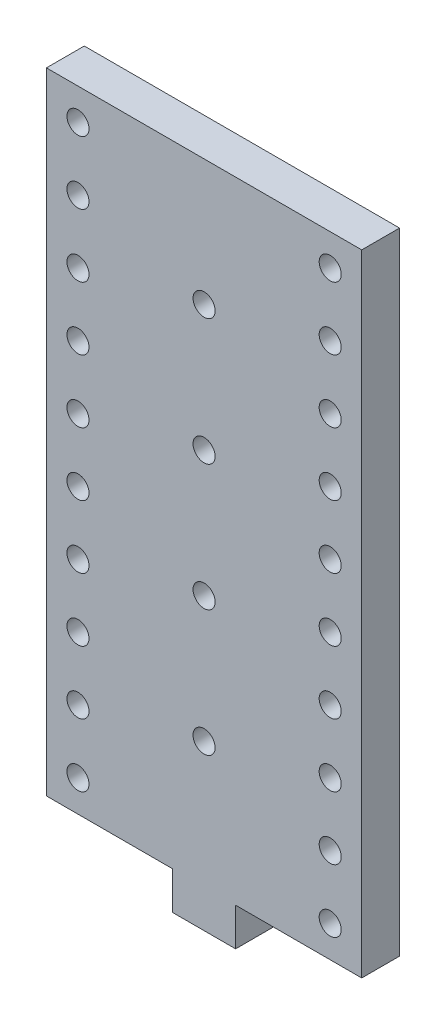
SolidWorks part; units mm, degrees
ref_plane "Plano frontal" through (0, 0, 0) normal (0, 0, 1) x (1, 0, 0)
ref_plane "Plano superior" through (0, 0, 0) normal (0, 1, 0) x (1, 0, 0)
ref_plane "Plano direito" through (0, 0, 0) normal (1, 0, 0) x (0, 0, -1)
sketch "Esboço1" plane through (0, 0, 0) normal (0, 0, 1) x (1, 0, 0)
  line L1 (20.6383, 0) -> (-29.3617, 0)
  line L2 (20.6383, 0) -> (20.6383, 100)
  line L3 (20.6383, 100) -> (-29.3617, 100)
  line L4 (-29.3617, 0) -> (-29.3617, 100)
  dimension "D1" = 100
  dimension "D2" = 50
extrude "Ressalto-extrusão1" add sketch "Esboço1" along normal blind 6
sketch "Esboço2" plane through (0, 0, 6) normal (0, 0, 1) x (1, 0, 0)
  line L0 (-24.3617, 100) -> (-24.3617, 0) construction
  line L1 (20.6383, 100) -> (-29.3617, 100) construction
  line L2 (-29.3617, 0) -> (20.6383, 0) construction
  line L3 (20.6383, 0) -> (20.6383, 100) construction
  line L4 (-29.3617, 100) -> (-29.3617, 0) construction
  line L6 (15.6383, 100.025) -> (15.6383, 0.025) construction
  circle A0 centre (-24.3617, 95) radius 1.75
  circle A1 centre (-24.3617, 85) radius 1.75
  circle A4 centre (-24.3617, 75) radius 1.75
  circle A5 centre (-24.3617, 65) radius 1.75
  circle A6 centre (-24.3617, 55) radius 1.75
  circle A7 centre (-24.3617, 45) radius 1.75
  circle A8 centre (-24.3617, 35) radius 1.75
  circle A9 centre (-24.3617, 25) radius 1.75
  circle A10 centre (-24.3617, 15) radius 1.75
  circle A11 centre (-24.3617, 5) radius 1.75
  circle A12 centre (15.6383, 95) radius 1.75
  circle A13 centre (15.6383, 85) radius 1.75
  circle A14 centre (15.6383, 75) radius 1.75
  circle A15 centre (15.6383, 65) radius 1.75
  circle A16 centre (15.6383, 55) radius 1.75
  circle A17 centre (15.6383, 45) radius 1.75
  circle A18 centre (15.6383, 35) radius 1.75
  circle A19 centre (15.6383, 25) radius 1.75
  circle A20 centre (15.6383, 15) radius 1.75
  circle A21 centre (15.6383, 5) radius 1.75
  dimension "D2" = 3.5
  dimension "D5" = 3.5
  dimension "D6" = 3.5
  dimension "D7" = 3.5
  dimension "D8" = 3.5
  dimension "D9" = 3.5
  dimension "D10" = 3.5
  dimension "D11" = 3.5
  dimension "D12" = 3.5
  dimension "D23" = 3.5
  dimension "D24" = 3.5
  dimension "D25" = 3.5
  dimension "D26" = 3.5
  dimension "D27" = 3.5
  dimension "D28" = 3.5
  dimension "D29" = 3.5
  dimension "D30" = 3.5
  dimension "D1" = 5
  dimension "D4" = 10
  dimension "D13" = 10
  dimension "D14" = 10
  dimension "D15" = 10
  dimension "D16" = 10
  dimension "D17" = 10
  dimension "D18" = 10
  dimension "D19" = 10
  dimension "D20" = 10
  dimension "D21" = 5
  dimension "D22" = 10
  dimension "D31" = 10
  dimension "D32" = 10
  dimension "D33" = 10
  dimension "D34" = 10
  dimension "D35" = 10
  dimension "D36" = 10
  dimension "D37" = 10
  dimension "D38" = 10
  dimension "D39" = 5
  dimension "D40" = 5
extrude "Corte-extrusão1" cut sketch "Esboço2" against normal through all both and the other way through all
sketch "Esboço3" plane through (0, 0, 6) normal (0, 0, 1) x (1, 0, 0)
  line L0 (-4.3617, 100) -> (-4.3617, 0) construction
  line L1 (20.6383, 100) -> (-29.3617, 100) construction
  line L2 (-29.3617, 0) -> (20.6383, 0) construction
  line L4 (-29.3617, 100) -> (-29.3617, 0) construction
  line L5 (20.6383, 0) -> (20.6383, 100) construction
  line L6 (-29.3617, 80) -> (20.6383, 80) construction
  line L7 (-29.3617, 60) -> (20.6383, 60) construction
  line L8 (-29.3617, 40) -> (20.6383, 40) construction
  line L9 (-29.3617, 20) -> (20.6383, 20) construction
  circle A1 centre (-4.3617, 80) radius 1.75
  circle A2 centre (-4.3617, 60) radius 1.75
  circle A3 centre (-4.3617, 40) radius 1.75
  circle A4 centre (-4.3617, 20) radius 1.75
  circle A5 centre (15.6383, 75) radius 1.75 construction
  circle A7 centre (15.6383, 55) radius 1.75 construction
  circle A8 centre (15.6383, 35) radius 1.75 construction
  circle A9 centre (15.6383, 15) radius 1.75 construction
  dimension "D1" = 3.5
  dimension "D2" = 3.5
  dimension "D3" = 3.5
  dimension "D4" = 3.5
  dimension "D5" = 5
  dimension "D6" = 5
  dimension "D7" = 5
  dimension "D8" = 5
extrude "Corte-extrusão2" cut sketch "Esboço3" against normal through all
sketch "Esboço4" plane through (0, 0, 0) normal (0, -1, 0) x (-1, 0, 0)
  line L0 (29.3617, -6) -> (-20.6383, -6) construction
  line L1 (9.3617, -6) -> (-0.6383, -6)
  line L2 (9.3617, -6) -> (9.3617, 0)
  line L3 (9.3617, 0) -> (-0.6383, 0)
  line L4 (-0.6383, -6) -> (-0.6383, 0)
  line L5 (29.3617, 0) -> (-20.6383, 0) construction
  line L7 (-20.6383, -6) -> (-20.6383, 0) construction
  line L8 (29.3617, -6) -> (29.3617, 0) construction
  dimension "D1" = 20
  dimension "D2" = 20
extrude "Ressalto-extrusão2" add sketch "Esboço4" along normal blind 6
